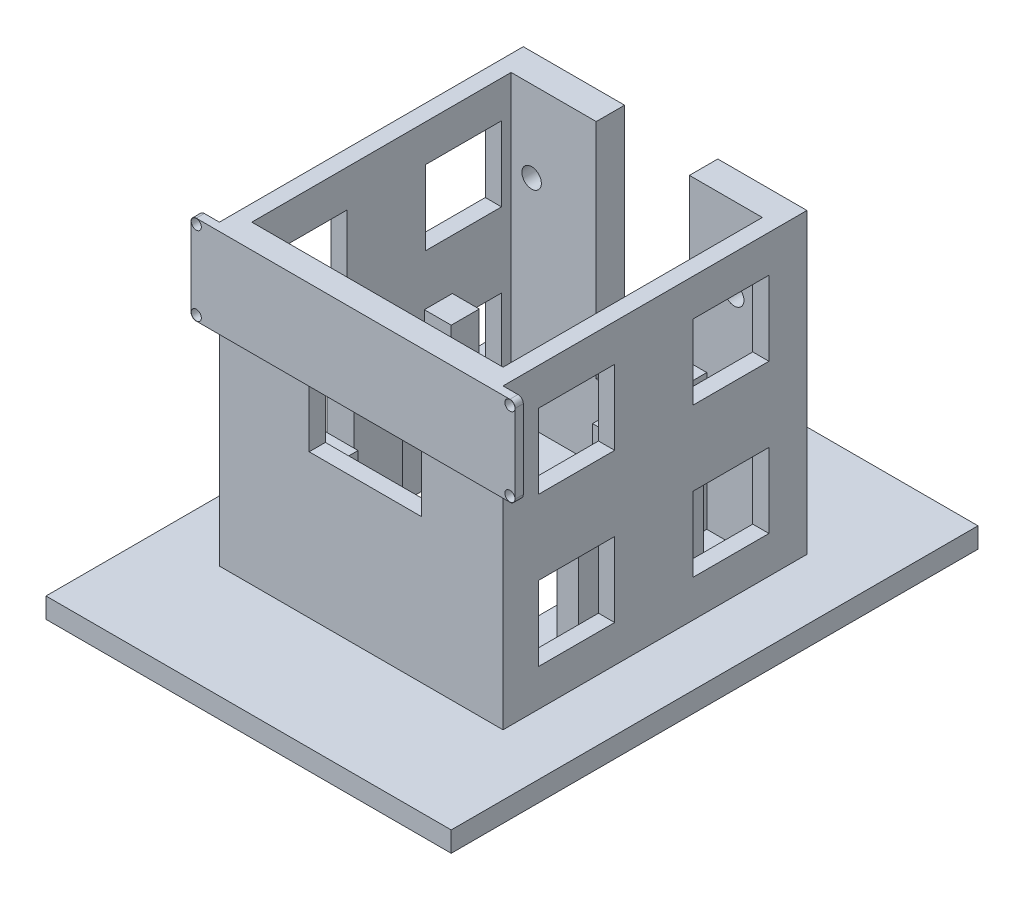
SolidWorks part; units mm, degrees
ref_plane "前视基准面" through (0, 0, 0) normal (0, 0, 1) x (1, 0, 0)
ref_plane "上视基准面" through (0, 0, 0) normal (0, 1, 0) x (1, 0, 0)
ref_plane "右视基准面" through (0, 0, 0) normal (1, 0, 0) x (0, 0, -1)
other "Configuration Table"
sketch "草图1" plane through (0, 0, 0) normal (0, 1, 0) x (1, 0, 0)
  line L0 (-112.425, 0) -> (170.9868, 0) construction
  line L1 (-50, -65) -> (50, -65)
  line L2 (-50, -65) -> (-50, 65)
  line L3 (-50, 65) -> (50, 65)
  line L4 (50, -65) -> (50, 65)
  line L7 (0, -111.328) -> (0, 89.4988) construction
  point P0 (0, 0)
  dimension "D1" = 130
  dimension "D2" = 100
extrude "凸台-拉伸1" add sketch "草图1" along normal blind 5
sketch "草图2" plane through (0, 5, 0) normal (0, 1, 0) x (1, 0, 0)
  line L1 (-35, -37.2143) -> (35, -37.2143)
  line L2 (-35, -37.2143) -> (-35, 37.7857)
  line L3 (-35, 37.7857) -> (35, 37.7857)
  line L4 (35, -37.2143) -> (35, 37.7857)
  line L7 (31, -33.2143) -> (-31, -33.2143)
  line L8 (31, -33.2143) -> (31, 30.7857)
  line L9 (31, 30.7857) -> (-31, 30.7857)
  line L10 (-31, -33.2143) -> (-31, 30.7857)
  line L11 (31, -33.2143) -> (-31, 30.7857) construction
  line L12 (31, 30.7857) -> (-31, -33.2143) construction
  point P0 (0, 0)
  point P6 (0, -1.2143)
  dimension "D1" = 70
  dimension "D2" = 75
  dimension "D3" = 4
  dimension "D4" = 4
  dimension "D5" = 7
extrude "凸台-拉伸2" add sketch "草图2" along normal blind 73.5
sketch "草图3" plane through (-35, 0, 0) normal (-1, 0, 0) x (0, 0, 1)
  line L0 (-55.6092, 41.75) -> (53.3676, 41.75) construction
  line L1 (0, -14.7642) -> (0, 89.0396) construction
  line L2 (-65, 5) -> (65, 5) construction
  line L3 (-37.7857, 78.5) -> (37.2143, 78.5) construction
  line L4 (-19.0357, 83.6874) -> (-19.0357, -11.6393) construction
  line L5 (19.0357, 83.6874) -> (19.0357, -11.6393) construction
  line L6 (-28.4107, 83.6874) -> (-28.4107, -8.1647) construction
  line L7 (28.4107, 83.6874) -> (28.4107, -8.1647) construction
  line L8 (-9.6607, 83.6874) -> (-9.6607, -8.1647) construction
  line L9 (9.6607, 83.6874) -> (9.6607, -8.1647) construction
  line L10 (-63.076, 60.15) -> (67.3523, 60.15) construction
  line L11 (-37.7857, 78.5) -> (-37.7857, 5) construction
  line L12 (-63.076, 23.35) -> (67.3523, 23.35) construction
  line L14 (-53.6144, 69.35) -> (51.4231, 69.35) construction
  line L15 (-53.6144, 14.15) -> (51.4231, 14.15) construction
  line L16 (-53.6144, 50.95) -> (51.4231, 50.95) construction
  line L17 (-53.6144, 32.55) -> (51.4231, 32.55) construction
  line L18 (-28.4107, 69.35) -> (-28.4107, 50.95)
  line L19 (-28.4107, 50.95) -> (-9.6607, 50.95)
  line L20 (-9.6607, 50.95) -> (-9.6607, 69.35)
  line L21 (-9.6607, 69.35) -> (-28.4107, 69.35)
  line L22 (9.6607, 50.95) -> (9.6607, 69.35)
  line L23 (28.4107, 50.95) -> (9.6607, 50.95)
  line L24 (28.4107, 69.35) -> (28.4107, 50.95)
  line L25 (9.6607, 69.35) -> (28.4107, 69.35)
  line L26 (28.4107, 32.55) -> (9.6607, 32.55)
  line L27 (28.4107, 14.15) -> (28.4107, 32.55)
  line L28 (9.6607, 14.15) -> (28.4107, 14.15)
  line L29 (9.6607, 32.55) -> (9.6607, 14.15)
  line L30 (-63.076, 23.35) -> (67.3523, 23.35) construction
  line L31 (-9.6607, 32.55) -> (-9.6607, 14.15)
  line L32 (-28.4107, 32.55) -> (-9.6607, 32.55)
  line L33 (-28.4107, 14.15) -> (-28.4107, 32.55)
  line L34 (-9.6607, 14.15) -> (-28.4107, 14.15)
  dimension "D1" = 18.75
  dimension "D2" = 9.375
  dimension "D3" = 18.4
  dimension "D4" = 9.2
extrude "切除-拉伸1" cut sketch "草图3" against normal through all
sketch "草图4" plane through (0, 0, -37.7857) normal (0, 0, -1) x (-1, 0, 0)
  line L0 (-35, 78.5) -> (35, 78.5) construction
  line L1 (-7, 23.5) -> (9.2301, 23.5) construction
  line L2 (-35, 78.5) -> (-35, 5) construction
  line L3 (-13, 78.5) -> (-13, 35.5)
  line L4 (-13, 35.5) -> (-13, 29.5)
  line L5 (-7, 23.5) -> (10, 23.5)
  line L6 (10, 78.5) -> (10, 23.5)
  line L7 (35, 78.5) -> (35, 5) construction
  line L8 (-13, 78.5) -> (10, 78.5)
  arc A0 (-13, 29.5) -> (-7, 23.5) centre (-7, 29.5) ccw
  dimension "D5" = 25
  dimension "D4" = 55
  dimension "D2" = 12
  dimension "D1" = 43
  dimension "D3" = 22
extrude "切除-拉伸2" cut sketch "草图4" against normal blind 10
sketch "草图7" plane through (0, 0, 0) normal (0, 1, 0) x (1, 0, 0)
  line L1 (-35, -37.2143) -> (35, -37.2143)
  line L2 (-35, -37.2143) -> (-35, 37.7857)
  line L3 (-35, 37.7857) -> (35, 37.7857)
  line L4 (35, -37.2143) -> (35, 37.7857)
  line L7 (31, -33.2143) -> (-31, -33.2143)
  line L8 (31, -33.2143) -> (31, 30.7857)
  line L9 (31, 30.7857) -> (-31, 30.7857)
  line L10 (-31, -33.2143) -> (-31, 30.7857)
  line L11 (31, -33.2143) -> (-31, 30.7857) construction
  line L12 (31, 30.7857) -> (-31, -33.2143) construction
  point P0 (0, 0)
  point P6 (0, -1.2143)
  dimension "D1" = 70
  dimension "D2" = 75
  dimension "D3" = 4
  dimension "D4" = 4
  dimension "D5" = 7
extrude "切除-拉伸3" cut sketch "草图7" along normal blind 3 contours L8 L7 L10 L9
sketch "草图8" plane through (0, 3, 0) normal (0, -1, 0) x (1, 0, 0)
  line L1 (15, -15) -> (-15, -15)
  line L2 (15, -15) -> (15, 15)
  line L3 (15, 15) -> (-15, 15)
  line L4 (-15, -15) -> (-15, 15)
  line L5 (15, -15) -> (-15, 15) construction
  line L6 (15, 15) -> (-15, -15) construction
  point P0 (0, 0)
  dimension "D1" = 30
  dimension "D2" = 30
extrude "切除-拉伸4" cut sketch "草图8" against normal blind 3
sketch "草图9" plane through (0, 3, 0) normal (0, -1, 0) x (1, 0, 0)
  line L0 (-64.601, 0) -> (73.6384, 0) construction
  line L1 (0, 38.7449) -> (0, -46.2426) construction
  circle A0 centre (-23, -23) radius 2.4
  circle A1 centre (23, -23) radius 2.4
  circle A2 centre (23, 23) radius 2.4
  circle A3 centre (-23, 23) radius 2.4
  dimension "D1" = 4.8
  dimension "D3" = 46
  dimension "D2" = 46
extrude "切除-拉伸5" cut sketch "草图9" against normal through all
sketch "草图11" plane through (0, 5, 0) normal (0, 1, 0) x (1, 0, 0)
  line L0 (-0.9119, 30.7857) -> (-0.9119, 20.7857)
  line L1 (-10, 30.7857) -> (7, 30.7857) construction
  line L2 (-0.9119, 20.7857) -> (13.2772, 20.7857)
  line L3 (13.2772, 20.7857) -> (13.2772, 30.7857)
  line L4 (31, 30.7857) -> (-31, 30.7857) construction
  line L5 (13.2772, 30.7857) -> (-0.9119, 30.7857)
  dimension "D1" = 10
extrude "凸台-拉伸3" add sketch "草图11" along normal up to surface (18.5 mm away) up to face at (-1.5, 23.5, -34.2857)
sketch "草图12" plane through (0, 5, 0) normal (0, 1, 0) x (1, 0, 0)
  line L1 (7, 30.7857) -> (13, 30.7857) construction
  line L2 (17.2862, 30.7857) -> (17.2862, 20.7857)
  line L7 (17.2862, 20.7857) -> (12.9349, 20.7857)
  line L8 (12.9349, 20.7857) -> (12.9349, 30.7857)
  line L9 (12.9349, 30.7857) -> (17.2862, 30.7857)
  dimension "D1" = 10
extrude "凸台-拉伸4" add sketch "草图12" along normal offset from surface (33.5 mm away) 40 up to face at (0.5, 78.5, -11.119)
sketch "草图13" plane through (0, 5, 0) normal (0, 1, 0) x (1, 0, 0)
  line L0 (-86.8041, 0) -> (87.8083, 0) construction
  line L1 (-23, 23) -> (-23, -39.5993) construction
  line L2 (0, 46.9334) -> (0, -57.2074) construction
  line L3 (23, -23) -> (-39.0023, -23) construction
  line L4 (23, 23) -> (23, -39.5993) construction
  line L5 (23, 23) -> (-39.0023, 23) construction
  line L6 (-31, 16.2877) -> (-24.3764, 16.2877)
  line L7 (-31, 30.7857) -> (-31, -33.2143) construction
  line L8 (-24.3764, 16.2877) -> (-24.3764, 9.3759)
  line L9 (-24.3764, 9.3759) -> (-31, 9.3759)
  line L10 (-31, 30.7857) -> (-31, -33.2143) construction
  line L11 (-31, -2.5866) -> (-24.3764, -2.5866)
  line L12 (-24.3764, -2.5866) -> (-24.3764, -14.6113)
  line L13 (-24.3764, -14.6113) -> (-31, -14.6113)
  line L14 (-31, -14.6113) -> (-31, -2.5866)
  line L15 (-31, 9.3759) -> (-31, 16.2877)
  line L16 (31, 16.2877) -> (25.6799, 16.2877)
  line L17 (31, -33.2143) -> (31, 30.7857) construction
  line L18 (25.6799, 16.2877) -> (25.6799, 9.3759)
  line L19 (25.6799, 9.3759) -> (31, 9.3759)
  line L20 (31, -33.2143) -> (31, 30.7857) construction
  line L21 (31, -2.5866) -> (25.6799, -2.5866)
  line L22 (25.6799, -2.5866) -> (25.6799, -14.6113)
  line L23 (25.6799, -14.6113) -> (31, -14.6113)
  line L24 (31, 16.2877) -> (31, 9.3759)
  line L25 (31, -2.5866) -> (31, -14.6113)
  line L26 (-17.7784, -33.2143) -> (-17.7784, -28.9041)
  line L27 (-31, -33.2143) -> (31, -33.2143) construction
  line L28 (-17.7784, -28.9041) -> (-9.0867, -28.9041)
  line L29 (-9.0867, -28.9041) -> (-9.0867, -33.2143)
  line L30 (-9.0867, -33.2143) -> (-17.7784, -33.2143)
  line L31 (10.2592, -33.2143) -> (10.2592, -28.9041)
  line L32 (10.2592, -28.9041) -> (19.8621, -28.9041)
  line L33 (19.8621, -28.9041) -> (19.8621, -33.2143)
  line L34 (-31, -33.2143) -> (31, -33.2143) construction
  line L35 (19.8621, -33.2143) -> (10.2592, -33.2143)
extrude "凸台-拉伸5" add sketch "草图13" along normal offset from surface (33.5 mm away) 40 up to face at (0.5, 78.5, -11.119)
sketch "草图14" plane through (0, 0, -37.7857) normal (0, 0, -1) x (-1, 0, 0)
  line L0 (-44.0735, 58.5) -> (49.0141, 58.5) construction
  line L1 (0.9411, -11.7752) -> (0.9411, 78.5) construction
  line L2 (31, 78.5) -> (-31, 78.5) construction
  line L3 (10, 78.5) -> (35, 78.5) construction
  circle A0 centre (-24.0589, 58.5) radius 2.4
  circle A1 centre (25.9411, 58.5) radius 2.4
  dimension "D2" = 4.8
  dimension "D1" = 20
  dimension "D3" = 50
extrude "切除-拉伸6" cut sketch "草图14" against normal blind 40
sketch "草图20" plane through (0, 0, 37.2143) normal (0, 0, 1) x (1, 0, 0)
  line L0 (0, -6.0396) -> (0, 83.0562) construction
  line L1 (-35, 78.5) -> (35, 78.5) construction
  line L2 (-38.7, 56.5) -> (38.7, 56.5)
  line L3 (-40, 57.8) -> (-40, 77.2)
  line L4 (-38.7, 78.5) -> (38.7, 78.5)
  line L5 (40, 57.8) -> (40, 77.2)
  line L6 (-40, 56.5) -> (40, 78.5) construction
  line L7 (-40, 78.5) -> (40, 56.5) construction
  arc A0 (40, 57.8) -> (38.7, 56.5) centre (38.7, 57.8) cw
  arc A1 (-40, 77.2) -> (-38.7, 78.5) centre (-38.7, 77.2) cw
  arc A2 (38.7, 78.5) -> (40, 77.2) centre (38.7, 77.2) cw
  arc A3 (-40, 57.8) -> (-38.7, 56.5) centre (-38.7, 57.8) ccw
  point P3 (0, 67.5)
  dimension "D3" = 1.3
  dimension "D4" = 1.3
  dimension "D1" = 80
  dimension "D2" = 22
extrude "凸台-拉伸8" add sketch "草图20" along normal blind 2
sketch "草图21" plane through (0, 0, 39.2143) normal (0, 0, 1) x (1, 0, 0)
  circle A0 centre (-38.7, 77.2) radius 1.25
  circle A1 centre (-38.7, 57.8) radius 1.25
  circle A2 centre (38.7, 77.2) radius 1.25
  circle A3 centre (38.7, 57.8) radius 1.25
  arc A4 (-38.7, 78.5) -> (-40, 77.2) centre (-38.7, 77.2) ccw construction
  arc A5 (-40, 57.8) -> (-38.7, 56.5) centre (-38.7, 57.8) ccw construction
  arc A6 (40, 77.2) -> (38.7, 78.5) centre (38.7, 77.2) ccw construction
  arc A7 (38.7, 56.5) -> (40, 57.8) centre (38.7, 57.8) ccw construction
  dimension "D1" = 2.5
extrude "切除-拉伸9" cut sketch "草图21" against normal blind 2
sketch "草图22" plane through (0, 0, 37.2143) normal (0, 0, 1) x (1, 0, 0)
  line L0 (-35, 56.5) -> (35, 56.5) construction
  line L1 (-12.8388, 40.5) -> (14.8257, 40.5)
  line L2 (-12.8388, 40.5) -> (-12.8388, 56.5)
  line L3 (-12.8388, 56.5) -> (14.8257, 56.5)
  line L4 (14.8257, 40.5) -> (14.8257, 56.5)
  line L5 (-12.8388, 40.5) -> (14.8257, 56.5) construction
  line L6 (-12.8388, 56.5) -> (14.8257, 40.5) construction
  line L7 (38.7, 78.5) -> (-38.7, 78.5) construction
  point P0 (0.9935, 48.5)
  dimension "D1" = 0
  dimension "D2" = 38
extrude "切除-拉伸10" cut sketch "草图22" against normal blind 5
sketch "草图23" plane through (0, 5, 0) normal (0, 1, 0) x (1, 0, 0)
  line L0 (-31, 9.3759) -> (-24.3764, 9.3759)
  line L1 (-24.3764, 9.3759) -> (-24.3764, -2.5866)
  line L2 (-24.3764, -2.5866) -> (-31, -2.5866)
  line L3 (-31, 9.3759) -> (-31, -2.5866) construction
  line L4 (-31, -2.5866) -> (-24.3764, -2.5866) construction
  line L5 (-31, -2.5866) -> (-31, 9.3759)
  line L6 (-9.0867, -28.9041) -> (10.2592, -28.9041)
  line L7 (10.2592, -28.9041) -> (10.2592, -33.2143)
  line L8 (10.2592, -33.2143) -> (-9.0867, -33.2143)
  line L9 (-9.0867, -33.2143) -> (-9.0867, -28.9041)
  line L10 (25.6799, 9.3759) -> (31, 9.3759)
  line L11 (31, 9.3759) -> (31, -2.5866)
  line L12 (31, -2.5866) -> (25.6799, -2.5866)
  line L13 (25.6799, -14.6113) -> (25.6799, -2.5866) construction
  line L14 (25.6799, -2.5866) -> (31, -2.5866) construction
  line L15 (25.6799, -2.5866) -> (25.6799, 9.3759)
extrude "切除-拉伸11" cut sketch "草图23" against normal through all
